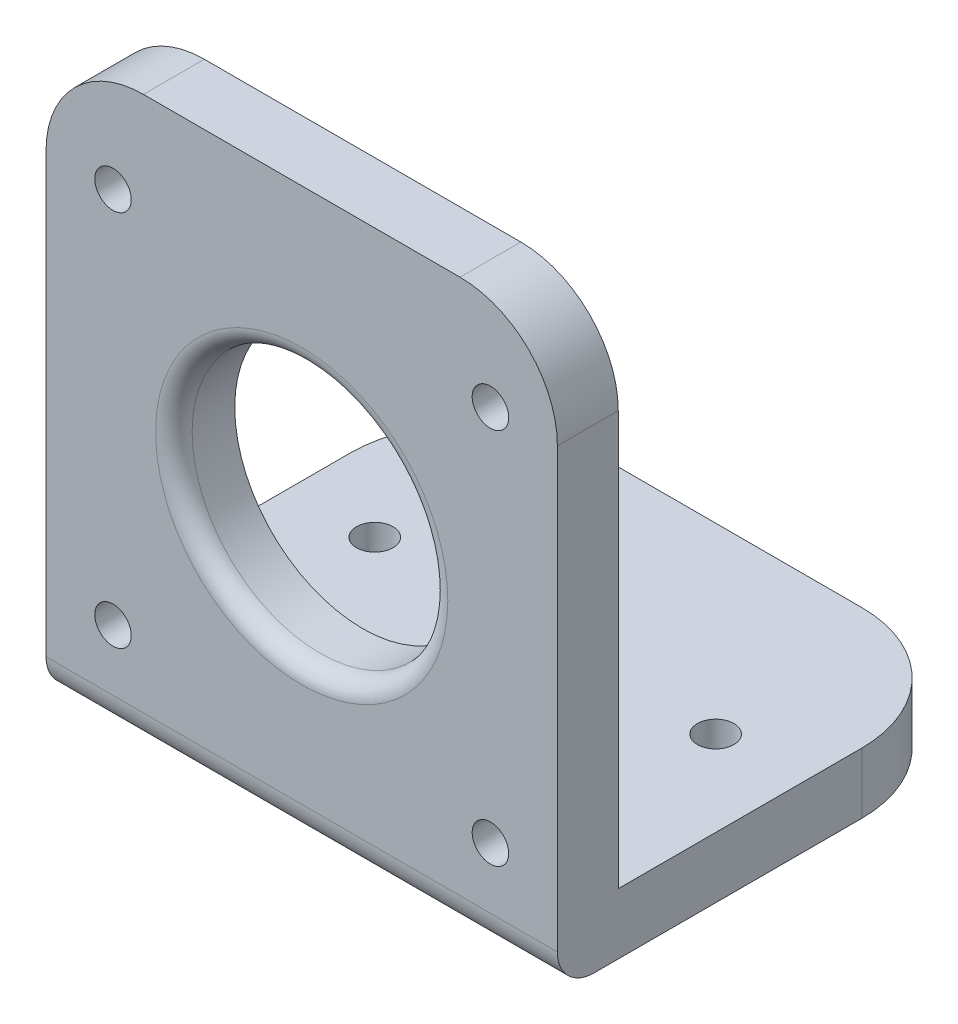
SolidWorks part; units mm, degrees
ref_plane "Plan de face" through (0, 0, 0) normal (0, 0, 1) x (1, 0, 0)
ref_plane "Plan de dessus" through (0, 0, 0) normal (0, 1, 0) x (1, 0, 0)
ref_plane "Plan de droite" through (0, 0, 0) normal (1, 0, 0) x (0, 0, -1)
sketch "Esquisse1" plane through (0, 0, 0) normal (0, 0, 1) x (1, 0, 0)
  line L1 (-13, 23.5) -> (13, 23.5)
  line L2 (-21, 15.5) -> (-21, -23.5)
  line L3 (-21, -23.5) -> (21, -23.5)
  line L4 (21, 15.5) -> (21, -23.5)
  line L5 (-21, 23.5) -> (21, -23.5) construction
  line L6 (-21, -23.5) -> (21, 23.5) construction
  circle A0 centre (0, 0) radius 10.5
  arc A1 (13, 23.5) -> (21, 15.5) centre (13, 15.5) cw
  arc A2 (-13, 23.5) -> (-21, 15.5) centre (-13, 15.5) ccw
  point P0 (0, 0)
  dimension "D3" = 21
  dimension "D4" = 8
  dimension "D1" = 42
  dimension "D2" = 47
extrude "Boss.-Extru.1" add sketch "Esquisse1" along normal blind 5
sketch "Esquisse2" plane through (0, 0, 0) normal (0, 0, -1) x (-1, 0, 0)
  line L0 (-21, -18.5) -> (21, -18.5)
  line L4 (-21, 15.5) -> (-21, -23.5)
  line L5 (-21, -23.5) -> (21, -23.5)
  line L6 (21, -23.5) -> (21, 15.5)
  line L7 (13, 23.5) -> (-13, 23.5)
  line L8 (-21, -18.5) -> (-21, -23.5)
  line L9 (-21, -23.5) -> (21, -23.5)
  line L10 (21, -23.5) -> (21, -18.5)
  arc A2 (21, 15.5) -> (13, 23.5) centre (13, 15.5) ccw
  arc A3 (-13, 23.5) -> (-21, 15.5) centre (-13, 15.5) ccw
  dimension "D2" = 5
  dimension "D1" = 0
extrude "Boss.-Extru.2" add sketch "Esquisse2" along normal blind 30
sketch "Esquisse3" plane through (0, -18.5, 0) normal (0, 1, 0) x (1, 0, 0)
  line L0 (-21, 15) -> (21, 15) construction
  line L1 (-21, 30) -> (-21, 0) construction
  line L2 (21, 30) -> (21, 0) construction
  line L3 (0, 30) -> (0, 0) construction
  line L4 (-21, 30) -> (21, 30) construction
  circle A0 centre (-14, 15) radius 1.5
  circle A1 centre (14, 15) radius 1.5
  point P13 (0, 30)
  dimension "D1" = 3
  dimension "D2" = 7
extrude "Enlèv. mat.-Extru.1" cut sketch "Esquisse3" against normal blind 30
fillet "Congé1" radius 10 2 edges at (21, -21, -30) (-21, -21, -30)
fillet "Congé2" radius 3 1 edges at (0, -23.5, 5)
sketch "Esquisse4" plane through (0, 0, 0) normal (0, 0, -1) x (-1, 0, 0)
  circle A0 centre (-15.5, 15.5) radius 1.5
  circle A1 centre (15.5, 15.5) radius 1.5
  circle A2 centre (-15.5, -15.5) radius 1.5
  circle A3 centre (15.5, -15.5) radius 1.5
extrude "Enlèv. mat.-Extru.2" cut sketch "Esquisse4" against normal through all
fillet "Congé3" radius 1.5 1 edges at (10.5, 0, 5)
